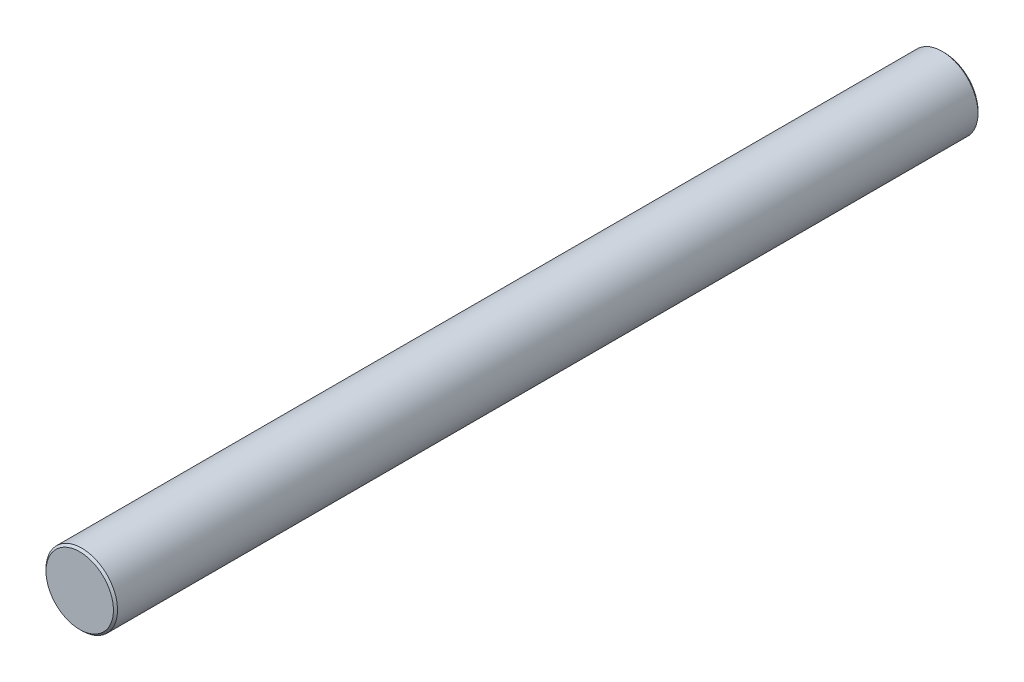
SolidWorks part; units mm, degrees
ref_plane "Front Plane" through (0, 0, 0) normal (0, 0, 1) x (1, 0, 0)
ref_plane "Top Plane" through (0, 0, 0) normal (0, 1, 0) x (1, 0, 0)
ref_plane "Right Plane" through (0, 0, 0) normal (1, 0, 0) x (0, 0, -1)
sketch "Sketch1" plane through (0, 0, 0) normal (0, 0, 1) x (1, 0, 0)
  circle A0 centre (0, 0) radius 3.475
  dimension "D1" = 6.95
extrude "Boss-Extrude1" add sketch "Sketch1" along normal mid plane 84
chamfer "Chamfer1" distance 0.2 angle 45 2 edges at (3.475, 0, -42) (3.475, 0, 42)
